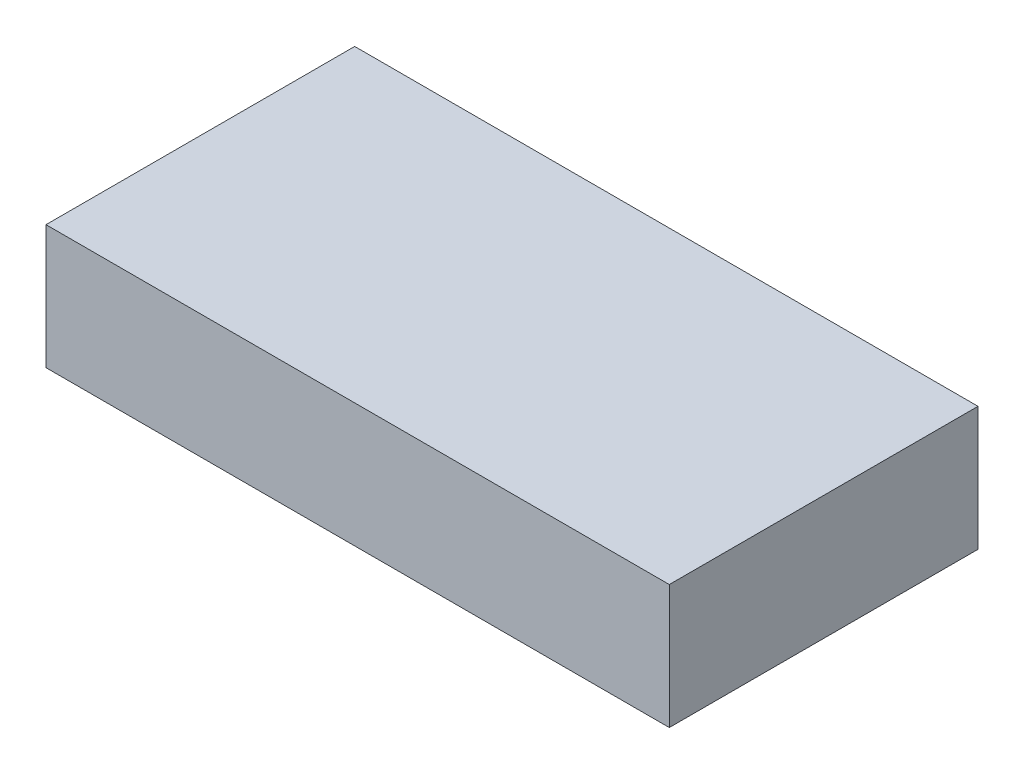
SolidWorks part; units mm, degrees
ref_plane "Front Plane" through (0, 0, 0) normal (0, 0, 1) x (1, 0, 0)
ref_plane "Top Plane" through (0, 0, 0) normal (0, 1, 0) x (1, 0, 0)
ref_plane "Right Plane" through (0, 0, 0) normal (1, 0, 0) x (0, 0, -1)
sketch "Sketch1" plane through (0, 0, 0) normal (0, 1, 0) x (1, 0, 0)
  line L1 (-7.925, 3.925) -> (7.925, 3.925)
  line L2 (-7.925, 3.925) -> (-7.925, -3.925)
  line L3 (-7.925, -3.925) -> (7.925, -3.925)
  line L4 (7.925, 3.925) -> (7.925, -3.925)
  line L5 (-7.925, 3.925) -> (7.925, -3.925) construction
  line L6 (-7.925, -3.925) -> (7.925, 3.925) construction
  point P0 (0, 0)
  dimension "D1" = 15.85
  dimension "D2" = 7.85
extrude "Boss-Extrude1" add sketch "Sketch1" against normal blind 3.15
shell "Shell1" thickness 1.5
